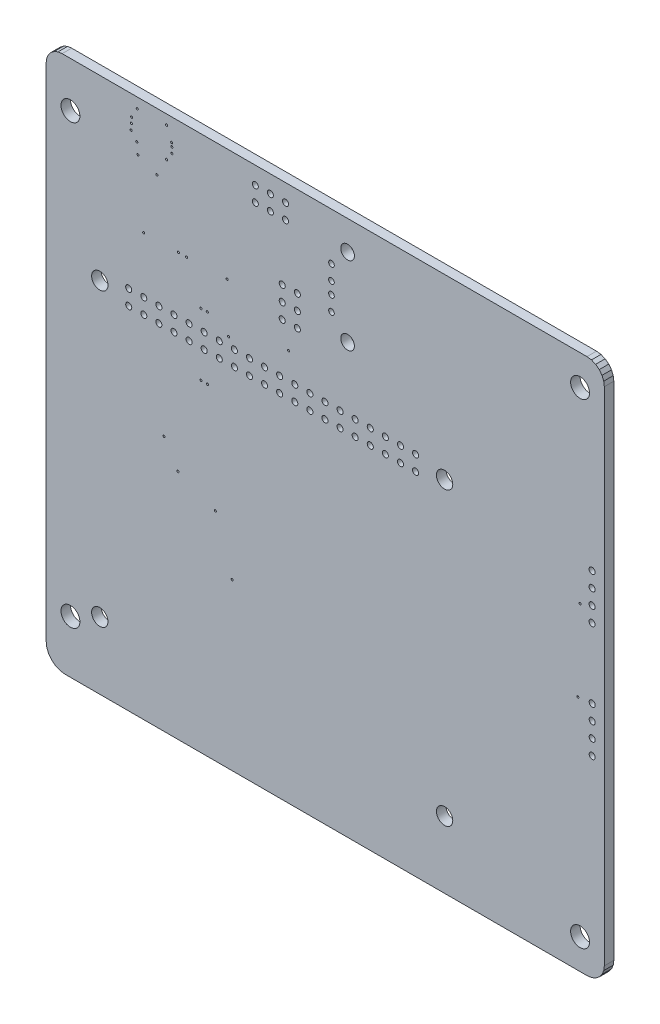
SolidWorks part; units mm, degrees
ref_plane "Plan de face" through (0, 0, 0) normal (0, 0, 1) x (1, 0, 0)
ref_plane "Plan de dessus" through (0, 0, 0) normal (0, 1, 0) x (1, 0, 0)
ref_plane "Plan de droite" through (0, 0, 0) normal (1, 0, 0) x (0, 0, -1)
ref_plane "Dielectric_Layer Couche 1" through (0, 0, 1.6) normal (0, 0, 1) x (1, 0, 0)
sketch "Esquisse1" plane through (0, 0, 0) normal (0, 0, 1) x (1, 0, 0)
  line L0 (0, 87.476) -> (0, 3.1945)
  line L1 (0, 3.1945) -> (0.1089, 2.3677)
  line L2 (0.1089, 2.3677) -> (0.428, 1.5973)
  line L3 (0.428, 1.5973) -> (0.9357, 0.9357)
  line L4 (0.9357, 0.9357) -> (1.5973, 0.428)
  line L5 (1.5973, 0.428) -> (2.3677, 0.1089)
  line L6 (2.3677, 0.1089) -> (3.1945, 0)
  line L7 (3.1945, 0) -> (91.0111, 0)
  line L8 (91.0111, 0) -> (91.7562, 0.0981)
  line L9 (91.7562, 0.0981) -> (92.4505, 0.3857)
  line L10 (92.4505, 0.3857) -> (93.0468, 0.8432)
  line L11 (93.0468, 0.8432) -> (93.5043, 1.4395)
  line L12 (93.5043, 1.4395) -> (93.7919, 2.1338)
  line L13 (93.7919, 2.1338) -> (93.89, 2.8789)
  line L14 (93.89, 2.8789) -> (93.89, 87.2525)
  line L15 (93.89, 87.2525) -> (93.7906, 88.0076)
  line L16 (93.7906, 88.0076) -> (93.4991, 88.7113)
  line L17 (93.4991, 88.7113) -> (93.0355, 89.3155)
  line L18 (93.0355, 89.3155) -> (92.4313, 89.7791)
  line L19 (92.4313, 89.7791) -> (91.7276, 90.0706)
  line L20 (91.7276, 90.0706) -> (90.9725, 90.17)
  line L21 (90.9725, 90.17) -> (2.694, 90.17)
  line L22 (2.694, 90.17) -> (1.9967, 90.0782)
  line L23 (1.9967, 90.0782) -> (1.347, 89.8091)
  line L24 (1.347, 89.8091) -> (0.7891, 89.3809)
  line L25 (0.7891, 89.3809) -> (0.3609, 88.823)
  line L26 (0.3609, 88.823) -> (0.0918, 88.1733)
  line L27 (0.0918, 88.1733) -> (0, 87.476)
extrude "Board_Outline" add sketch "Esquisse1" along normal blind 1.6 separate body
sketch "Esquisse2" plane through (0, 0, 0) normal (0, 0, 1) x (1, 0, 0)
  circle A0 centre (4.08, 8.89) radius 1.59
  circle A1 centre (89.81, 5.08) radius 1.59
  circle A2 centre (89.81, 85.09) radius 1.59
  circle A3 centre (4.08, 82.55) radius 1.59
  circle A4 centre (9.02, 11.27) radius 1.375
  circle A5 centre (67.02, 11.27) radius 1.375
  circle A6 centre (9.02, 60.27) radius 1.375
  circle A7 centre (67.02, 60.27) radius 1.375
  circle A8 centre (50.7014, 72.1304) radius 1.15
  circle A9 centre (50.7014, 85.2704) radius 1.15
  circle A10 centre (89.4403, 39.8087) radius 0.175
  circle A11 centre (15.24, 83.5914) radius 0.175
  circle A12 centre (20.2438, 83.5152) radius 0.175
  circle A13 centre (15.4432, 81.8134) radius 0.175
  circle A14 centre (18.6182, 80.4926) radius 0.175
  circle A15 centre (15.3162, 88.4428) radius 0.175
  circle A16 centre (20.2438, 88.5444) radius 0.175
  circle A17 centre (14.3764, 86.7664) radius 0.175
  circle A18 centre (14.3256, 85.852) radius 0.175
  circle A19 centre (14.3002, 84.8106) radius 0.175
  circle A20 centre (21.1074, 86.4362) radius 0.175
  circle A21 centre (21.1328, 85.8012) radius 0.175
  circle A22 centre (21.1328, 84.836) radius 0.175
  circle A23 centre (30.4292, 71.1708) radius 0.175
  circle A24 centre (19.8374, 42.9768) radius 0.175
  circle A25 centre (16.4084, 70.9168) radius 0.175
  circle A26 centre (22.1742, 39.0398) radius 0.175
  circle A27 centre (28.455, 36.445) radius 0.175
  circle A28 centre (31.2928, 27.8384) radius 0.175
  circle A29 centre (26.03, 64.7206) radius 0.175
  circle A30 centre (26.0362, 54.2606) radius 0.175
  circle A31 centre (27.1, 64.76) radius 0.175
  circle A32 centre (27.12, 54.2306) radius 0.175
  circle A33 centre (30.6959, 62.9259) radius 0.175
  circle A34 centre (40.76, 65.94) radius 0.175
  circle A35 centre (89.8178, 53.6042) radius 0.175
  circle A36 centre (22.2632, 71) radius 0.175
  circle A37 centre (23.6162, 70.9838) radius 0.175
extrude "NPTH" cut sketch "Esquisse2" along normal through all
sketch "Esquisse3" plane through (0, 0, 0) normal (0, 0, 1) x (1, 0, 0)
  circle A0 centre (91.83, 51.79) radius 0.51
  circle A1 centre (91.83, 54.33) radius 0.51
  circle A2 centre (91.83, 56.87) radius 0.51
  circle A3 centre (91.83, 59.41) radius 0.51
  circle A4 centre (91.85, 32.44) radius 0.51
  circle A5 centre (91.85, 34.98) radius 0.51
  circle A6 centre (91.85, 37.52) radius 0.51
  circle A7 centre (91.85, 40.06) radius 0.51
  circle A8 centre (35.18, 84.71) radius 0.51
  circle A9 centre (35.18, 87.25) radius 0.51
  circle A10 centre (37.72, 84.71) radius 0.51
  circle A11 centre (37.72, 87.25) radius 0.51
  circle A12 centre (40.26, 84.71) radius 0.51
  circle A13 centre (40.26, 87.25) radius 0.51
  circle A14 centre (39.71, 75.02) radius 0.51
  circle A15 centre (42.25, 75.02) radius 0.51
  circle A16 centre (39.71, 72.48) radius 0.51
  circle A17 centre (42.25, 72.48) radius 0.51
  circle A18 centre (39.71, 69.94) radius 0.51
  circle A19 centre (42.25, 69.94) radius 0.51
  circle A20 centre (13.89, 59) radius 0.51
  circle A21 centre (13.88, 61.54) radius 0.51
  circle A22 centre (16.42, 59) radius 0.51
  circle A23 centre (16.42, 61.54) radius 0.51
  circle A24 centre (18.96, 59) radius 0.51
  circle A25 centre (18.96, 61.54) radius 0.51
  circle A26 centre (21.5, 59) radius 0.51
  circle A27 centre (21.5, 61.54) radius 0.51
  circle A28 centre (24.04, 59) radius 0.51
  circle A29 centre (24.04, 61.54) radius 0.51
  circle A30 centre (26.58, 59) radius 0.51
  circle A31 centre (26.58, 61.54) radius 0.51
  circle A32 centre (29.12, 59) radius 0.51
  circle A33 centre (29.12, 61.54) radius 0.51
  circle A34 centre (31.66, 59) radius 0.51
  circle A35 centre (31.66, 61.54) radius 0.51
  circle A36 centre (34.2, 59) radius 0.51
  circle A37 centre (34.2, 61.54) radius 0.51
  circle A38 centre (36.74, 59) radius 0.51
  circle A39 centre (36.74, 61.54) radius 0.51
  circle A40 centre (39.28, 59) radius 0.51
  circle A41 centre (39.28, 61.54) radius 0.51
  circle A42 centre (41.82, 59) radius 0.51
  circle A43 centre (41.82, 61.54) radius 0.51
  circle A44 centre (44.36, 59) radius 0.51
  circle A45 centre (44.36, 61.54) radius 0.51
  circle A46 centre (46.9, 59) radius 0.51
  circle A47 centre (46.9, 61.54) radius 0.51
  circle A48 centre (49.44, 59) radius 0.51
  circle A49 centre (49.44, 61.54) radius 0.51
  circle A50 centre (51.98, 59) radius 0.51
  circle A51 centre (51.98, 61.54) radius 0.51
  circle A52 centre (54.52, 59) radius 0.51
  circle A53 centre (54.52, 61.54) radius 0.51
  circle A54 centre (57.06, 59) radius 0.51
  circle A55 centre (57.06, 61.54) radius 0.51
  circle A56 centre (59.6, 59) radius 0.51
  circle A57 centre (59.6, 61.54) radius 0.51
  circle A58 centre (62.14, 59) radius 0.51
  circle A59 centre (62.14, 61.54) radius 0.51
  circle A60 centre (47.99, 75.2) radius 0.475
  circle A61 centre (47.99, 77.7) radius 0.475
  circle A62 centre (47.99, 79.7) radius 0.475
  circle A63 centre (47.99, 82.2) radius 0.475
extrude "PTH" cut sketch "Esquisse3" along normal through all
